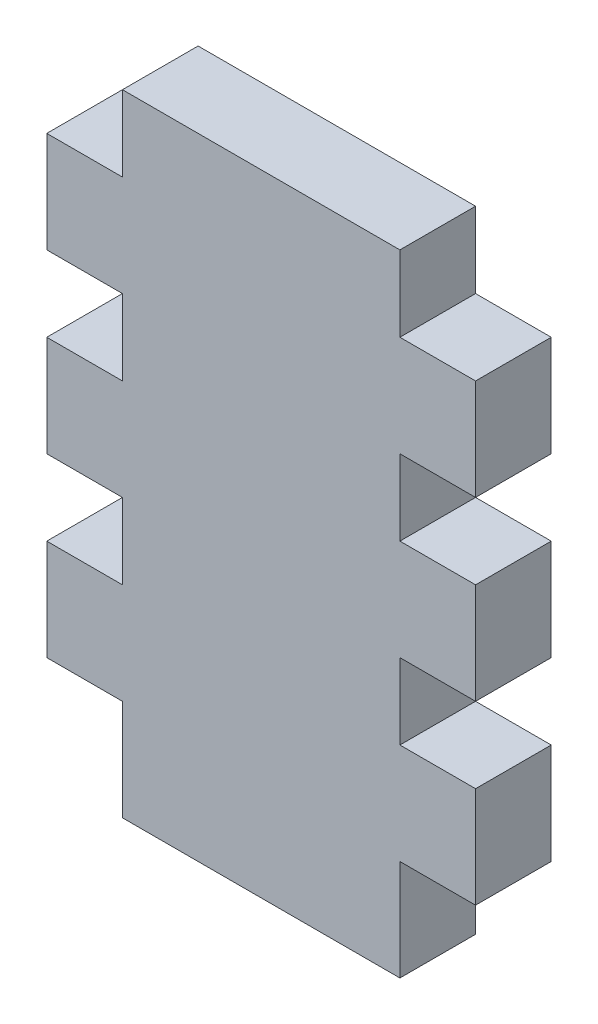
SolidWorks part; units mm, degrees
ref_plane "Plan de face" through (0, 0, 0) normal (0, 0, 1) x (1, 0, 0)
ref_plane "Plan de dessus" through (0, 0, 0) normal (0, 1, 0) x (1, 0, 0)
ref_plane "Plan de droite" through (0, 0, 0) normal (1, 0, 0) x (0, 0, -1)
sketch "Sketch1" plane through (0, 0, 0) normal (0, 0, 1) x (1, 0, 0)
  line L1 (-7, -12.5) -> (7, -12.5)
  line L2 (-7, -12.5) -> (-7, 12.5)
  line L3 (-7, 12.5) -> (7, 12.5)
  line L4 (7, -12.5) -> (7, 12.5)
  line L5 (-7, -12.5) -> (7, 12.5) construction
  line L6 (-7, 12.5) -> (7, -12.5) construction
  point P0 (0, 0)
  dimension "D1" = 14
  dimension "D2" = 25
extrude "Boss-Extrude1" add sketch "Sketch1" along normal blind 3
sketch "Sketch3" plane through (0, 0, 3) normal (0, 0, 1) x (1, 0, 0)
  line L0 (-7, 12.5) -> (-7, -12.5) construction
  line L1 (-7, 9.5) -> (-4, 9.5)
  line L2 (-7, 9.5) -> (-7, 12.5)
  line L3 (-7, 12.5) -> (-4, 12.5)
  line L4 (-4, 9.5) -> (-4, 12.5)
  line L5 (7, 12.5) -> (-7, 12.5) construction
  line L7 (-7, 5.5) -> (-4, 5.5)
  line L8 (-7, 5.5) -> (-7, 2.5)
  line L9 (-7, 2.5) -> (-4, 2.5)
  line L10 (-4, 5.5) -> (-4, 2.5)
  line L11 (-7, -1.5) -> (-4, -1.5)
  line L12 (-7, -1.5) -> (-7, -4.5)
  line L13 (-7, -4.5) -> (-4, -4.5)
  line L14 (-4, -1.5) -> (-4, -4.5)
  line L15 (-7, -8.5) -> (-4, -8.5)
  line L16 (-7, -8.5) -> (-7, -12.5)
  line L17 (-7, -12.5) -> (-4, -12.5)
  line L18 (-4, -8.5) -> (-4, -12.5)
  dimension "D1" = 3
  dimension "D2" = 3
  dimension "D3" = 3
  dimension "D4" = 3
  dimension "D5" = 4
  dimension "D6" = 3
  dimension "D7" = 3
  dimension "D8" = 4
  dimension "D9" = 4
  dimension "D10" = 3
  dimension "D11" = 4
extrude "Cut-Extrude2" cut sketch "Sketch3" against normal blind 3
sketch "Sketch4" plane through (0, 0, 3) normal (0, 0, 1) x (1, 0, 0)
  line L0 (7, -12.5) -> (7, 12.5) construction
  line L1 (7, 9.5) -> (10, 9.5)
  line L2 (7, 9.5) -> (7, 5.5)
  line L3 (7, 5.5) -> (10, 5.5)
  line L4 (10, 9.5) -> (10, 5.5)
  line L5 (7, 12.5) -> (-4, 12.5) construction
  line L7 (7, 2.5) -> (10, 2.5)
  line L8 (7, 2.5) -> (7, -1.5)
  line L9 (7, -1.5) -> (10, -1.5)
  line L10 (10, 2.5) -> (10, -1.5)
  line L11 (7, -4.5) -> (10, -4.5)
  line L12 (7, -4.5) -> (7, -8.5)
  line L13 (7, -8.5) -> (10, -8.5)
  line L14 (10, -4.5) -> (10, -8.5)
  point P6 (8.5, 9.5)
  dimension "D1" = 3
  dimension "D2" = 4
  dimension "D3" = 3
  dimension "D4" = 3
  dimension "D5" = 4
  dimension "D6" = 3
  dimension "D7" = 4
  dimension "D8" = 3
  dimension "D9" = 3
extrude "Boss-Extrude2" add sketch "Sketch4" against normal blind 3
